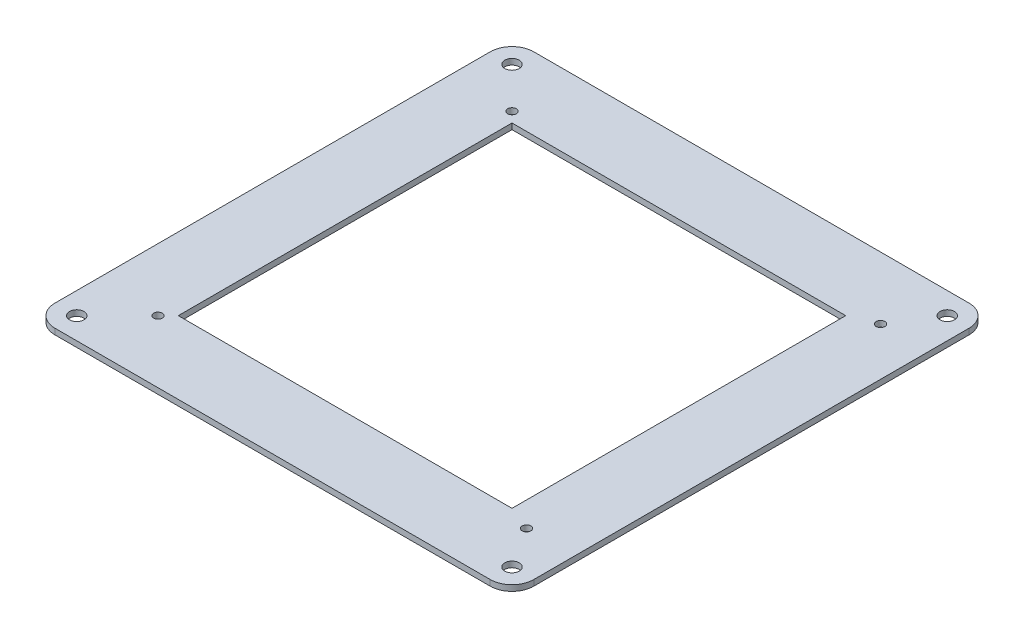
SolidWorks part; units mm, degrees
ref_plane "Alzado" through (0, 0, 0) normal (0, 0, 1) x (1, 0, 0)
ref_plane "Planta" through (0, 0, 0) normal (0, 1, 0) x (1, 0, 0)
ref_plane "Vista lateral" through (0, 0, 0) normal (1, 0, 0) x (0, 0, -1)
sketch "Croquis1" plane through (0, 0, 0) normal (0, 1, 0) x (1, 0, 0)
  line L0 (-85, 85) -> (85, 85)
  line L1 (-75, -75) -> (75, -75) construction
  line L2 (-75, -75) -> (-75, 75) construction
  line L3 (-75, 75) -> (75, 75) construction
  line L4 (75, -75) -> (75, 75) construction
  line L5 (-75, -75) -> (75, 75) construction
  line L6 (-75, 75) -> (75, -75) construction
  line L7 (85, -85) -> (85, 85)
  line L8 (-85, -85) -> (85, -85)
  line L9 (-85, -85) -> (-85, 85)
  line L10 (-61, 0) -> (-61, -61) construction
  line L11 (0, 0) -> (-61, 0) construction
  line L12 (0, 0) -> (0, 61) construction
  line L13 (0, 61) -> (-61, 61) construction
  line L14 (-61, 0) -> (-61, 61) construction
  line L15 (0, 0) -> (66, 0)
  line L16 (0, 0) -> (0, 61)
  line L17 (0, 61) -> (66, 61) construction
  line L18 (66, 0) -> (66, 61) construction
  line L19 (-61, -61) -> (66, -61) construction
  line L20 (66, -61) -> (66, 0) construction
  line L22 (-57.5, -57.5) -> (57.5, -57.5)
  line L23 (-57.5, -57.5) -> (-57.5, 57.5)
  line L24 (-57.5, 57.5) -> (57.5, 57.5)
  line L25 (57.5, -57.5) -> (57.5, 57.5)
  line L26 (-57.5, -57.5) -> (57.5, 57.5) construction
  line L27 (-57.5, 57.5) -> (57.5, -57.5) construction
  circle A0 centre (-75, 75) radius 2.5
  circle A1 centre (75, 75) radius 2.5
  circle A2 centre (75, -75) radius 2.5
  circle A3 centre (-75, -75) radius 2.5
  circle A4 centre (-61, 61) radius 1.5
  circle A5 centre (66, 61) radius 1.5
  circle A6 centre (66, -61) radius 1.5
  circle A7 centre (-61, -61) radius 1.5
  point P0 (0, 0)
  dimension "D3" = 5
  dimension "D6" = 3
  dimension "D1" = 150
  dimension "D2" = 10
  dimension "D4" = 61
  dimension "D5" = 66
  dimension "D7" = 115
extrude "Saliente-Extruir1" add sketch "Croquis1" along normal blind 2
sketch "Croquis2" plane through (0, 2, 0) normal (0, 1, 0) x (1, 0, 0)
  line L0 (-75, 75) -> (75, -75) construction
  line L1 (-75, 75) -> (-85, 85) construction
  line L2 (-85, 85) -> (85, 85) construction
  line L3 (-85, 85) -> (-85, -85) construction
  line L4 (-85, -85) -> (85, -85) construction
  line L5 (85, 85) -> (85, -85) construction
  line L6 (75, -75) -> (85, -85) construction
  point P8 (-133.6031, 133.6031)
  dimension "D1" = 170
sketch "Croquis3" plane through (0, 2, 0) normal (0, 1, 0) x (1, 0, 0)
  line L0 (-75, 75) -> (75, -75) construction
  line L1 (75, -82.5) -> (-75, -82.5)
  line L2 (82.5, -75) -> (82.5, 75)
  line L3 (75, 82.5) -> (-75, 82.5)
  line L4 (-82.5, -75) -> (-82.5, 75)
  line L5 (80, -80) -> (-80, 80) construction
  line L6 (80, 80) -> (-80, -80) construction
  line L7 (-85, -85) -> (85, -85) construction
  line L8 (-85, 85) -> (-85, -85) construction
  line L9 (-85, 85) -> (85, 85) construction
  line L10 (85, 85) -> (85, -85) construction
  line L11 (-85, -85) -> (85, -85)
  line L12 (-85, 85) -> (-85, -85)
  line L13 (-85, 85) -> (85, 85)
  line L14 (85, 85) -> (85, -85)
  arc A0 (-75, 82.5) -> (-82.5, 75) centre (-75, 75) ccw
  arc A1 (82.5, 75) -> (75, 82.5) centre (75, 75) ccw
  arc A2 (75, -82.5) -> (82.5, -75) centre (75, -75) ccw
  arc A3 (-82.5, -75) -> (-75, -82.5) centre (-75, -75) ccw
  point P3 (0, 0)
  dimension "D1" = 15
extrude "Cortar-Extruir1" cut sketch "Croquis3" against normal blind 10
